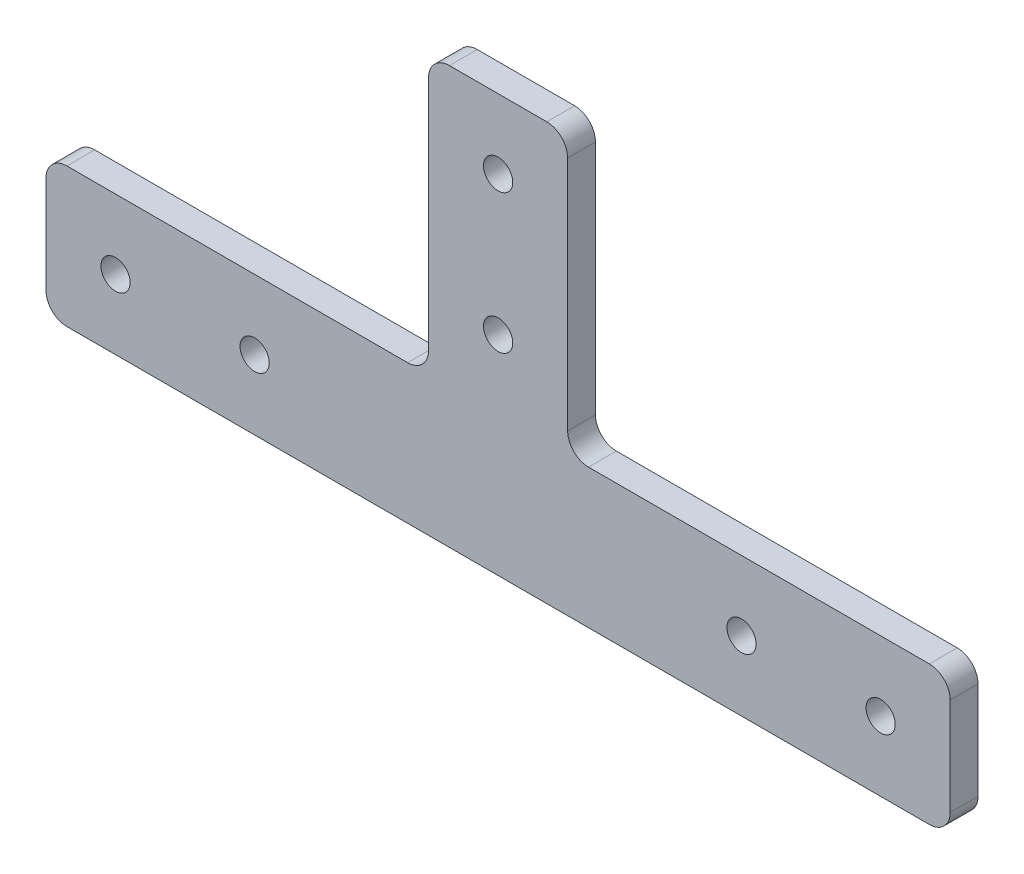
SolidWorks part; units mm, degrees
ref_plane "前视基准面" through (0, 0, 0) normal (0, 0, 1) x (1, 0, 0)
ref_plane "上视基准面" through (0, 0, 0) normal (0, 1, 0) x (1, 0, 0)
ref_plane "右视基准面" through (0, 0, 0) normal (1, 0, 0) x (0, 0, -1)
sketch "草图1" plane through (0, 0, 0) normal (0, 0, 1) x (1, 0, 0)
  line L0 (-10, 10) -> (-10, 50)
  line L1 (-65, 10) -> (65, 10)
  line L2 (-65, 10) -> (-65, -10)
  line L3 (-65, -10) -> (65, -10)
  line L4 (65, 10) -> (65, -10)
  line L5 (-65, 10) -> (65, -10) construction
  line L6 (-65, -10) -> (65, 10) construction
  line L7 (-10, 50) -> (10, 50)
  line L8 (10, 50) -> (10, 10)
  line L9 (0, 10) -> (0, -10) construction
  circle A0 centre (-55, 0) radius 2.1
  circle A1 centre (-35, 0) radius 2.1
  circle A2 centre (35, 0) radius 2.1
  circle A3 centre (55, 0) radius 2.1
  circle A4 centre (0, 40) radius 2.1
  circle A6 centre (0, 20) radius 2.1
  point P0 (0, 0)
  point P8 (0, 10)
  dimension "D6" = 10
  dimension "D8" = 4.2
  dimension "D9" = 4.2
  dimension "D11" = 4.2
  dimension "D13" = 10
  dimension "D14" = 4.2
  dimension "D1" = 20
  dimension "D2" = 130
  dimension "D3" = 20
  dimension "D4" = 10
  dimension "D5" = 40
  dimension "D7" = 10
  dimension "D10" = 20
  dimension "D12" = 20
extrude "凸台-拉伸1" add sketch "草图1" along normal blind 4 contours L4 L1 L2 L3 A2 A1 A0 A3 | L8 L7 L0 L1 A6 A4
fillet "圆角1" radius 3 8 edges at (-65, -10, 2) (-65, 10, 2) (65, -10, 2) (65, 10, 2) (-10, 50, 2) (10, 50, 2) (-10, 10, 2) (10, 10, 2)
